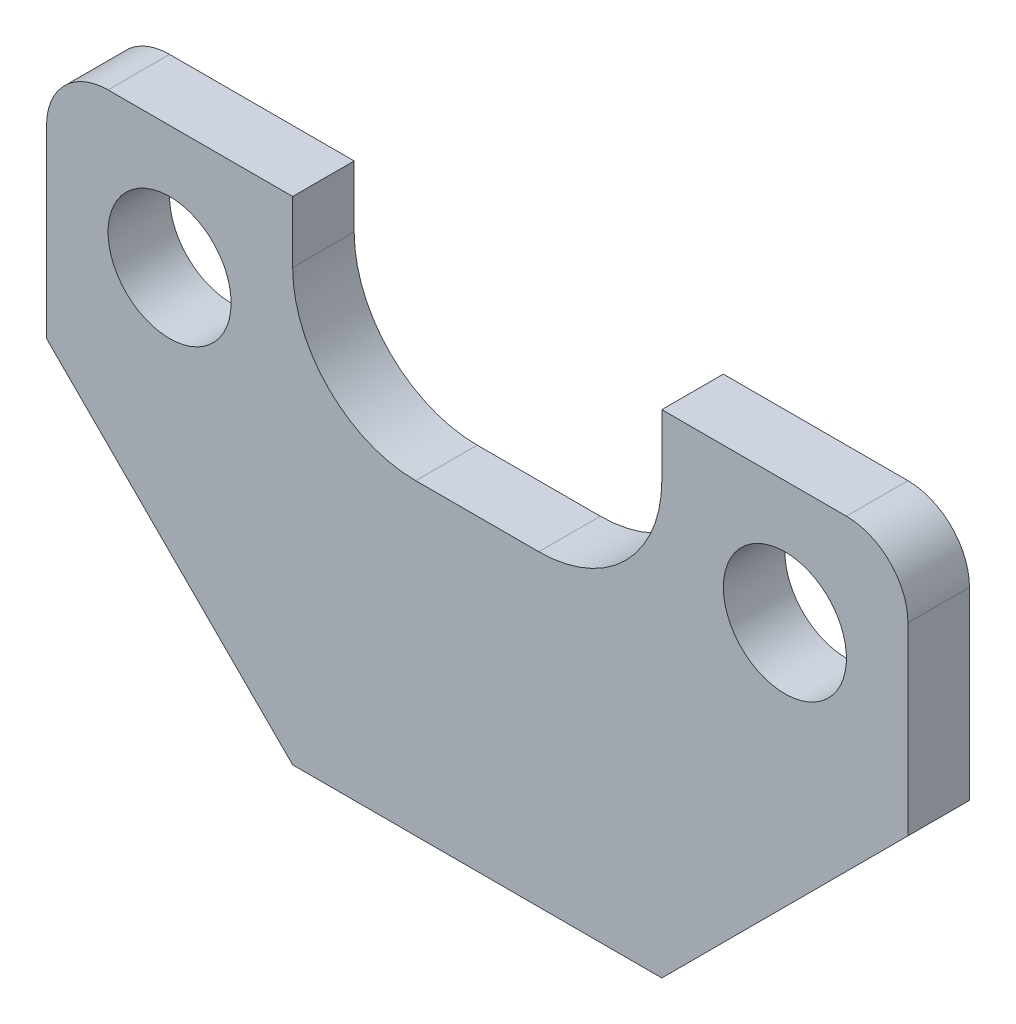
SolidWorks part; units mm, degrees
ref_plane "Front Plane" through (0, 0, 0) normal (0, 0, 1) x (1, 0, 0)
ref_plane "Top Plane" through (0, 0, 0) normal (0, 1, 0) x (1, 0, 0)
ref_plane "Right Plane" through (0, 0, 0) normal (1, 0, 0) x (0, 0, -1)
sketch "Sketch1" plane through (0, 0, 0) normal (0, 0, 1) x (1, 0, 0)
  line L0 (-35, 0) -> (-15, -20)
  line L1 (-30, 20) -> (-15, 20)
  line L2 (-35, 15) -> (-35, 0)
  line L3 (-15, -20) -> (15, -20)
  line L4 (35, 15) -> (35, 0)
  line L5 (-35, 20) -> (35, -20) construction
  line L6 (-35, -20) -> (35, 20) construction
  line L7 (0, 25.9916) -> (0, -34.3525) construction
  line L8 (35, 0) -> (15, -20)
  line L9 (-15, 20) -> (-15, 15)
  line L10 (-5, 5) -> (5, 5)
  line L11 (15, 15) -> (15, 20)
  line L12 (15, 20) -> (30, 20)
  arc A0 (35, 15) -> (30, 20) centre (30, 15) ccw
  arc A1 (-30, 20) -> (-35, 15) centre (-30, 15) ccw
  arc A2 (15, 15) -> (5, 5) centre (5, 15) cw
  arc A3 (-5, 5) -> (-15, 15) centre (-5, 15) cw
  circle A4 centre (-25, 10) radius 5
  circle A5 centre (25, 10) radius 5
  point P0 (0, 0)
  dimension "D5" = 5
  dimension "D7" = 10
  dimension "D9" = 10
  dimension "D11" = 10
  dimension "D1" = 70
  dimension "D2" = 40
  dimension "D3" = 20
  dimension "D4" = 20
  dimension "D6" = 30
  dimension "D8" = 15
  dimension "D10" = 10
extrude "Boss-Extrude1" add sketch "Sketch1" along normal blind 5
